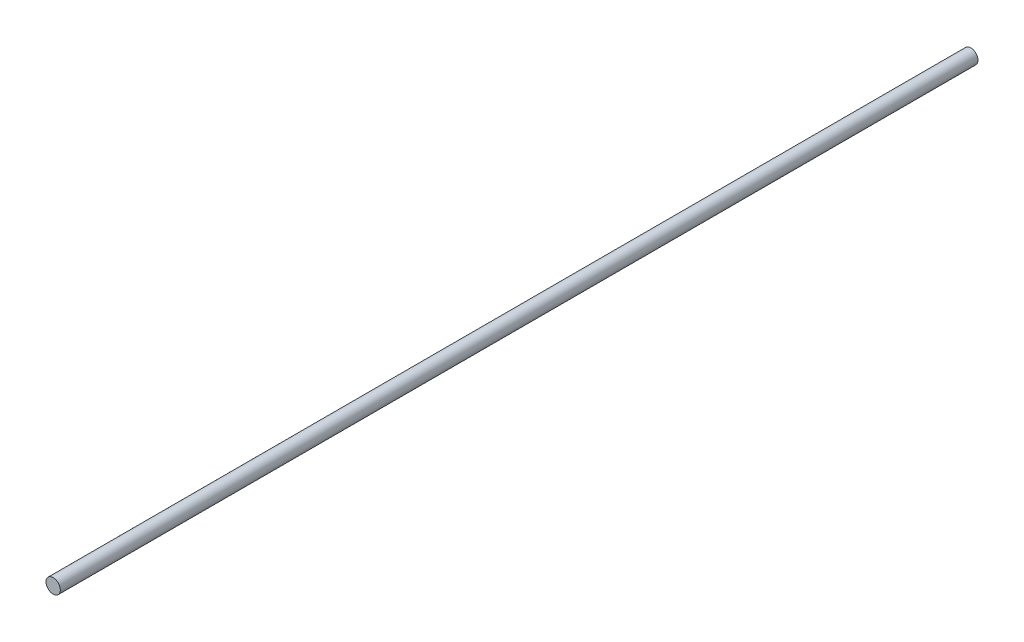
SolidWorks part; units mm, degrees
ref_plane "Front Plane" through (0, 0, 0) normal (0, 0, 1) x (1, 0, 0)
ref_plane "Top Plane" through (0, 0, 0) normal (0, 1, 0) x (1, 0, 0)
ref_plane "Right Plane" through (0, 0, 0) normal (1, 0, 0) x (0, 0, -1)
sketch "Sketch1" plane through (0, 0, 0) normal (0, 0, 1) x (1, 0, 0)
  circle A0 centre (0, 0) radius 1.5875
  dimension "D1" = 3.175
extrude "Boss-Extrude1" add sketch "Sketch1" along normal mid plane 203.2
